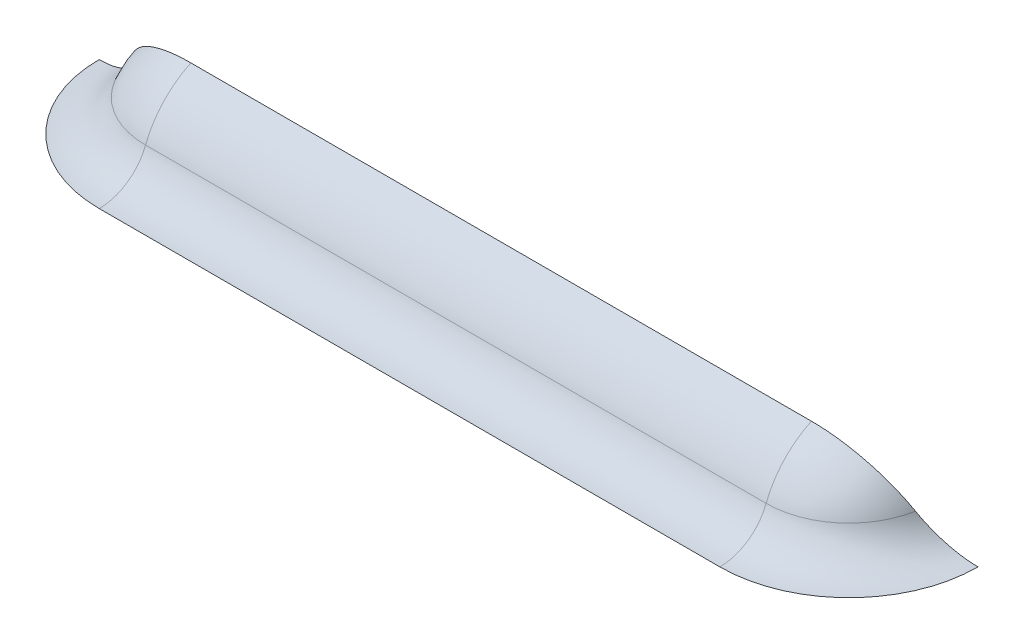
SolidWorks part; units mm, degrees
ref_plane "front" through (0, 0, 0) normal (0, 0, 1) x (1, 0, 0)
ref_plane "top" through (0, 0, 0) normal (0, 1, 0) x (1, 0, 0)
ref_plane "side" through (0, 0, 0) normal (1, 0, 0) x (0, 0, -1)
sketch "Sketch1" plane through (0, 0, 0) normal (1, 0, 0) x (0, 0, -1)
  line L0 (-25.4, 0) -> (25.4, 0)
  line L1 (-25.4, 0) -> (-25.4, 3.4642)
  line L2 (25.4, 3.4642) -> (-25.4, 3.4642)
  line L3 (25.4, 3.4642) -> (25.4, 0)
  line L4 (0, 0) -> (0, 3.4642) construction
  dimension "D1" = 50.8
  dimension "D2" = 3.4642
extrude "Base-Extrude" add sketch "Sketch1" along normal mid plane 101.6
sketch "Sketch3" plane through (0, 4.665, 2.5812) normal (1, 0, 0) x (0, 0, 1)
  line L0 (-4.547, 1.2007) -> (-4.547, -4.2437)
  line L2 (-4.547, 1.2007) -> (0.8974, 1.2007)
  line L4 (0.8974, 1.2007) -> (0.8974, 3.4642) construction
  line L5 (-27.9812, 1.2007) -> (22.8188, 1.2007) construction
  line L6 (-4.547, -4.2437) -> (-3.0249, -4.2437) construction
  line L8 (-1.8248, 13.7033) -> (-1.8248, 1.2007) construction
  arc A0 (-4.547, -4.2437) -> (0.8974, 1.2007) centre (-4.547, 1.2007) ccw
extrude "Boss-Extrude1" add sketch "Sketch3" along normal mid plane 38.1
sketch "Sketch4" plane through (-19.05, 0, 0) normal (-1, 0, 0) x (0, 0, 1)
  line L0 (-1.9658, 3.4642) -> (-1.9658, 8.9087) construction
  line L2 (-1.9658, 3.4642) -> (3.4786, 3.4642)
  line L3 (-1.9658, 8.9087) -> (-1.9658, 3.4642)
  line L4 (-1.9658, 3.4642) -> (3.4786, 3.4642)
  line L5 (-1.9658, 8.9087) -> (-1.9658, 3.4642)
  arc A1 (3.4786, 3.4642) -> (-1.9658, 8.9087) centre (-1.9658, 3.4642) ccw
  arc A2 (3.4786, 3.4642) -> (-1.9658, 8.9087) centre (-1.9658, 3.4642) ccw
  dimension "D1" = 0
revolve "Boss-Revolve1" add sketch "Sketch4" angle 90 about L0
mirror "Mirror1" about plane through (0, 0, 0) normal (1, 0, 0) of "Boss-Revolve1"
fillet "Fillet1" radius 3.048 3 edges at (0, 3.4642, 3.4786) (-22.8998, 3.4642, 1.884) (22.8998, 3.4642, 1.884)
sketch "Sketch7" plane through (0, 0, 0) normal (1, 0, 0) x (0, 0, -1)
  line L0 (1.9658, 3.4642) -> (-0.3351, 8.3986)
  line L3 (1.9658, 5.4183) -> (1.9658, 8.9087) construction
  line L4 (1.9658, 3.4642) -> (1.9658, 8.9087)
  line L5 (25.4, 3.4642) -> (-25.4, 3.4642) construction
  line L7 (1.9658, 3.4642) -> (1.9658, 8.9087)
  line L8 (-3.4786, 3.4642) -> (1.9658, 3.4642)
  arc A0 (1.9658, 8.9087) -> (-3.1159, 5.4183) centre (1.9658, 3.4642) ccw construction
  arc A2 (1.9658, 8.9087) -> (-3.4786, 3.4642) centre (1.9658, 3.4642) ccw
  arc A3 (1.9658, 8.9087) -> (-0.3351, 8.3986) centre (1.9658, 3.4642) ccw
  dimension "D1" = 25
  dimension "D2" = 0
extrude "Cut-Extrude2" cut sketch "Sketch7" against normal through all and the other way through all
sketch "Sketch5" plane through (-50.8, 0, 0) normal (-1, 0, 0) x (0, 0, 1)
  line L4 (25.4, 0) -> (25.4, 3.4642)
  line L5 (25.4, 3.4642) -> (-25.4, 3.4642)
  line L6 (-25.4, 3.4642) -> (-25.4, 0)
  line L7 (-25.4, 0) -> (25.4, 0)
  line L8 (25.4, 0) -> (25.4, 3.4642)
  line L9 (25.4, 3.4642) -> (-25.4, 3.4642)
  line L10 (-25.4, 3.4642) -> (-25.4, 0)
  line L11 (-25.4, 0) -> (25.4, 0)
  dimension "D1" = 0
extrude "Cut-Extrude1" cut sketch "Sketch5" against normal through all
sketch "Orientation sketch" plane through (0, 3.4642, 0) normal (0, -1, 0) x (1, 0, 0)
  line L2 (19.05, 5.9608) -> (-19.05, 5.9608)
  line L3 (-26.9766, -1.9658) -> (26.9766, -1.9658)
  line L4 (19.05, 5.9608) -> (-19.05, 5.9608)
  line L5 (-26.9766, -1.9658) -> (26.9766, -1.9658)
  arc A2 (26.9766, -1.9658) -> (19.05, 5.9608) centre (19.05, -1.9658) ccw
  arc A3 (-19.05, 5.9608) -> (-26.9766, -1.9658) centre (-19.05, -1.9658) ccw
  arc A4 (26.9766, -1.9658) -> (19.05, 5.9608) centre (19.05, -1.9658) ccw
  arc A5 (-19.05, 5.9608) -> (-26.9766, -1.9658) centre (-19.05, -1.9658) ccw
  dimension "D1" = 0
